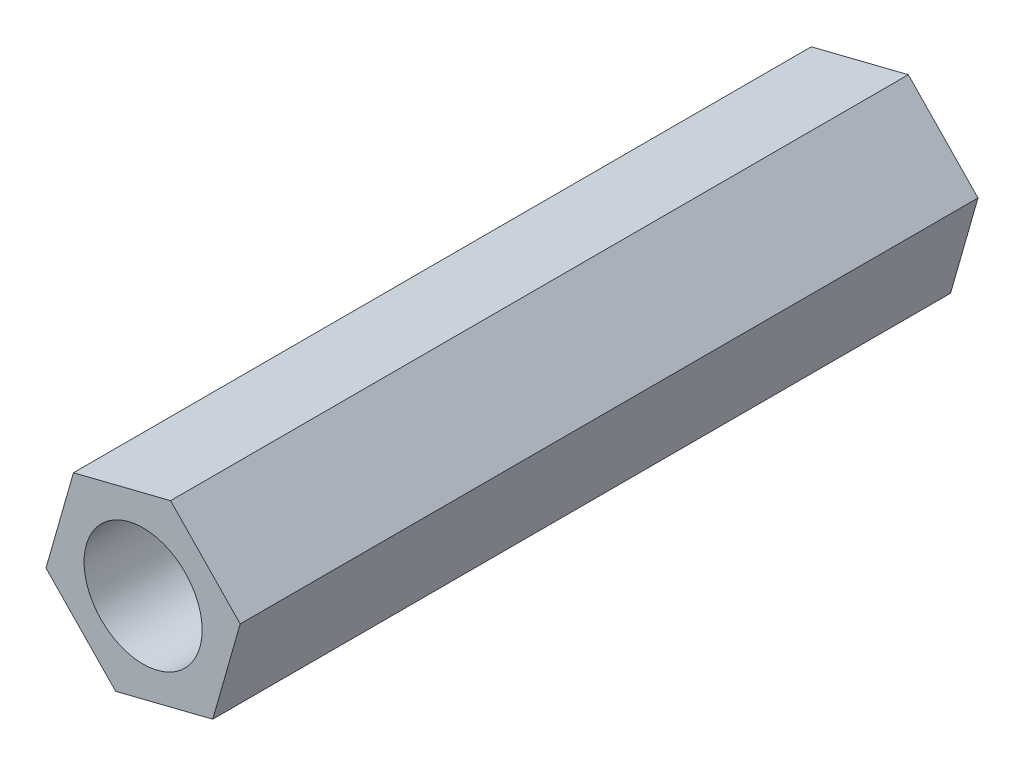
SolidWorks part; units mm, degrees
ref_plane "Front Plane" through (0, 0, 0) normal (0, 0, 1) x (1, 0, 0)
ref_plane "Top Plane" through (0, 0, 0) normal (0, 1, 0) x (1, 0, 0)
ref_plane "Right Plane" through (0, 0, 0) normal (1, 0, 0) x (0, 0, -1)
sketch "Sketch1" plane through (0, 0, 0) normal (0, 0, 1) x (1, 0, 0)
  line L1 (1.8879, -1.9492) -> (2.632, 0.6604)
  line L2 (2.632, 0.6604) -> (0.7441, 2.6095)
  line L3 (0.7441, 2.6095) -> (-1.8879, 1.9492)
  line L4 (-1.8879, 1.9492) -> (-2.632, -0.6604)
  line L5 (-2.632, -0.6604) -> (-0.7441, -2.6095)
  line L6 (-0.7441, -2.6095) -> (1.8879, -1.9492)
  circle A0 centre (0, 0) radius 2.35 construction
  circle A1 centre (0, 0) radius 1.6
  dimension "D2" = 3.2
  dimension "D1" = 4.7
extrude "Boss-Extrude1" add sketch "Sketch1" along normal blind 20
